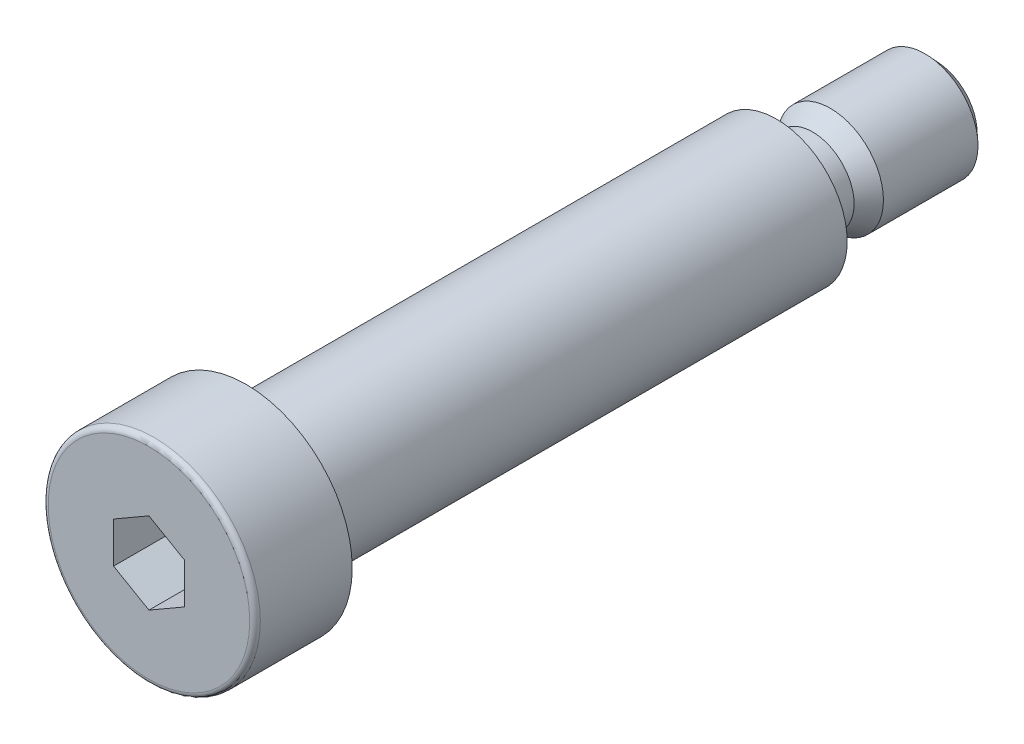
SolidWorks part; units mm, degrees
material "1.0545 (S355N)"
ref_plane "Płaszczyzna przednia" through (0, 0, 0) normal (0, 0, 1) x (1, 0, 0)
ref_plane "Płaszczyzna górna" through (0, 0, 0) normal (0, 1, 0) x (1, 0, 0)
ref_plane "Płaszczyzna prawa" through (0, 0, 0) normal (1, 0, 0) x (0, 0, -1)
sketch "Szkic1" plane through (0, 0, 0) normal (0, 1, 0) x (1, 0, 0)
  line L0 (6, 36.1) -> (4.7, 34.08)
  line L1 (12, -41) -> (-12, -41)
  line L2 (12, -41) -> (12, -30)
  line L3 (12, -30) -> (-12, -30)
  line L4 (-12, -41) -> (-12, -30)
  line L5 (8, -30) -> (-8, -30)
  line L6 (8, -30) -> (8, 30)
  line L7 (8, 30) -> (-8, 30)
  line L8 (-8, -30) -> (-8, 30)
  line L9 (-4.7, 30) -> (4.7, 30)
  line L10 (-4.7, 30) -> (-4.7, 34.08)
  line L11 (-4.7, 34.08) -> (4.7, 34.08)
  line L12 (4.7, 30) -> (4.7, 34.08)
  line L13 (6, 36.1) -> (6, 46.8)
  line L14 (6, 46.8) -> (4.7, 48)
  line L15 (4.7, 48) -> (-4.7, 48)
  line L16 (-4.7, 48) -> (-6, 46.8)
  line L17 (-6, 46.8) -> (-6, 36.1)
  line L18 (-6, 36.1) -> (-4.7, 34.08)
  line L19 (6, 36.1) -> (-6, 36.1) construction
  line L20 (6, 46.8) -> (-6, 46.8) construction
  line L21 (0, -19.9356) -> (0, 25.6583) construction
  line L22 (0, -41) -> (0, 48)
  point P4 (0, -30)
  point P14 (0, -30)
  point P15 (0, 30)
  point P16 (0, 30)
  point P17 (-8, 0)
  point P23 (0, 36.1)
  point P25 (0, 48)
  point P26 (0, 34.08)
  point P27 (0, 46.8)
  dimension "D1" = 24
  dimension "D2" = 11
  dimension "D3" = 16
  dimension "l1" = 60
  dimension "D5" = 9.4
  dimension "D6" = 18
  dimension "D7" = 12
  dimension "D8" = 9.4
  dimension "D9" = 1.2
  dimension "D10" = 2.02
  dimension "D11" = 10.7
revolve "Obrót1" add sketch "Szkic1" angle 360 about L22
sketch "Szkic2" plane through (0, 0, 41) normal (0, 0, 1) x (1, 0, 0)
  line L1 (4, 2.3094) -> (0, 4.6188)
  line L2 (0, 4.6188) -> (-4, 2.3094)
  line L3 (-4, 2.3094) -> (-4, -2.3094)
  line L4 (-4, -2.3094) -> (0, -4.6188)
  line L5 (0, -4.6188) -> (4, -2.3094)
  line L6 (4, -2.3094) -> (4, 2.3094)
  circle A0 centre (0, 0) radius 4 construction
  dimension "D1" = 8
extrude "Wytnij-wyciągnięcie1" cut sketch "Szkic2" against normal blind 6.6
fillet "Zaokrąglenie1" radius 0.6 1 edges at (12, 0, 41)
